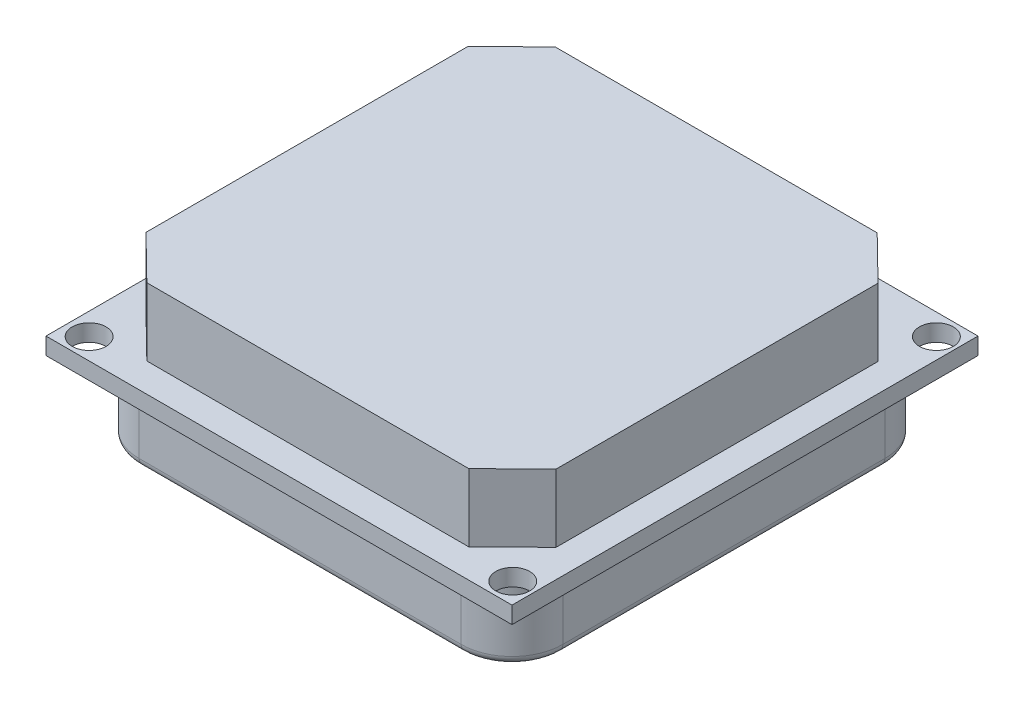
SolidWorks part; units mm, degrees
ref_plane "前视基准面" through (0, 0, 0) normal (0, 0, 1) x (1, 0, 0)
ref_plane "上视基准面" through (0, 0, 0) normal (0, 1, 0) x (1, 0, 0)
ref_plane "右视基准面" through (0, 0, 0) normal (1, 0, 0) x (0, 0, -1)
sketch "草图1" plane through (0, 0, 0) normal (0, 1, 0) x (1, 0, 0)
  line L0 (13.75, 13.75) -> (13.75, -13.75)
  line L1 (13.75, 13.75) -> (-13.75, 13.75)
  line L2 (13.75, -13.75) -> (-13.75, -13.75)
  line L3 (-13.75, 13.75) -> (-13.75, -13.75)
  line L4 (13.75, 13.75) -> (-13.75, -13.75) construction
  line L5 (13.75, -13.75) -> (-13.75, 13.75) construction
  point P1 (0, 0)
  dimension "D1" = 27.5
extrude "凸台-拉伸1" add sketch "草图1" along normal blind 1
sketch "草图2" plane through (0, 1, 0) normal (0, 1, 0) x (1, 0, 0)
  circle A0 centre (-12.448, 12.4921) radius 1
  circle A1 centre (12.552, 12.4921) radius 1
  circle A2 centre (12.552, -12.5079) radius 1
  circle A3 centre (-12.448, -12.5079) radius 1
  dimension "D1" = 2
  dimension "D2" = 25
  dimension "D3" = 25
  dimension "D4" = 25
extrude "切除-拉伸1" cut sketch "草图2" against normal blind 1
sketch "草图3" plane through (0, 1, 0) normal (0, 1, 0) x (1, 0, 0)
  line L0 (-18.153, 0) -> (24.6455, 0) construction
  line L1 (-12.1, 9.5) -> (12.1, 9.5) construction
  line L2 (-12.1, 9.5) -> (-12.1, -9.5) construction
  line L3 (-12.1, -9.5) -> (12.1, -9.5) construction
  line L4 (12.1, 9.5) -> (12.1, -9.5) construction
  line L5 (-9.5, 12.05) -> (9.5, 12.05) construction
  line L6 (-9.5, 12.05) -> (-9.5, -12.05) construction
  line L7 (-9.5, -12.05) -> (9.5, -12.05) construction
  line L8 (9.5, 12.05) -> (9.5, -12.05) construction
  line L9 (0, 19.6915) -> (0, -21.3937) construction
  line L10 (-9.5, 12.05) -> (-12.1, 9.5)
  line L11 (-12.1, 9.5) -> (-12.1, -9.5)
  line L12 (-12.1, -9.5) -> (-9.5, -12.05)
  line L13 (-9.5, -12.05) -> (9.5, -12.05)
  line L14 (9.5, -12.05) -> (12.1, -9.5)
  line L15 (12.1, -9.5) -> (12.1, 9.5)
  line L16 (12.1, 9.5) -> (9.5, 12.05)
  line L17 (9.5, 12.05) -> (-9.5, 12.05)
  dimension "D1" = 24.1
  dimension "D2" = 24.2
  dimension "D3" = 19
  dimension "D4" = 19
extrude "凸台-拉伸2" add sketch "草图3" along normal blind 4
sketch "草图4" plane through (0, 0, 0) normal (0, -1, 0) x (1, 0, 0)
  line L0 (0, 17.8523) -> (0, -18.8197) construction
  line L1 (-12.5, 9.5) -> (12.5, 9.5) construction
  line L2 (-12.5, 9.5) -> (-12.5, -9.5) construction
  line L3 (-12.5, -9.5) -> (12.5, -9.5) construction
  line L4 (12.5, 9.5) -> (12.5, -9.5) construction
  line L5 (-9.5, 12.5) -> (9.5, 12.5) construction
  line L6 (-9.5, 12.5) -> (-9.5, -12.5) construction
  line L7 (-9.5, -12.5) -> (9.5, -12.5) construction
  line L8 (9.5, 12.5) -> (9.5, -12.5) construction
  line L9 (-21.0877, 0) -> (21.5542, 0) construction
  line L10 (-9.5, 12.5) -> (9.5, 12.5)
  line L11 (12.5, 9.5) -> (12.5, -9.5)
  line L12 (9.5, -12.5) -> (-9.5, -12.5)
  line L13 (-12.5, -9.5) -> (-12.5, 9.5)
  arc A0 (9.5, 12.5) -> (12.5, 9.5) centre (9.5, 9.5) cw
  arc A1 (12.5, -9.5) -> (9.5, -12.5) centre (9.5, -9.5) cw
  arc A2 (-9.5, -12.5) -> (-12.5, -9.5) centre (-9.5, -9.5) cw
  arc A3 (-12.5, 9.5) -> (-9.5, 12.5) centre (-9.5, 9.5) cw
  dimension "D1" = 25
  dimension "D2" = 25
  dimension "D3" = 19
  dimension "D4" = 19
extrude "凸台-拉伸3" add sketch "草图4" along normal blind 4.26
sketch "草图5" plane through (0, -4.26, 0) normal (0, -1, 0) x (1, 0, 0)
  line L0 (12.5, -9.5) -> (12.5, 9.5) construction
  line L2 (9.5, 12.5) -> (-9.5, 12.5) construction
  circle A0 centre (2.5, 0.5) radius 1.6
  dimension "D1" = 3.2
  dimension "D2" = 10
  dimension "D3" = 12
extrude "凸台-拉伸4" add sketch "草图5" along normal blind 0.3
fillet "圆角1" radius 0.5 8 edges at (-11.6213, -4.26, 11.6213) (0, -4.26, 12.5) (11.6213, -4.26, 11.6213) (12.5, -4.26, 0) (11.6213, -4.26, -11.6213) (-12.5, -4.26, 0) (-11.6213, -4.26, -11.6213) (0, -4.26, -12.5)
